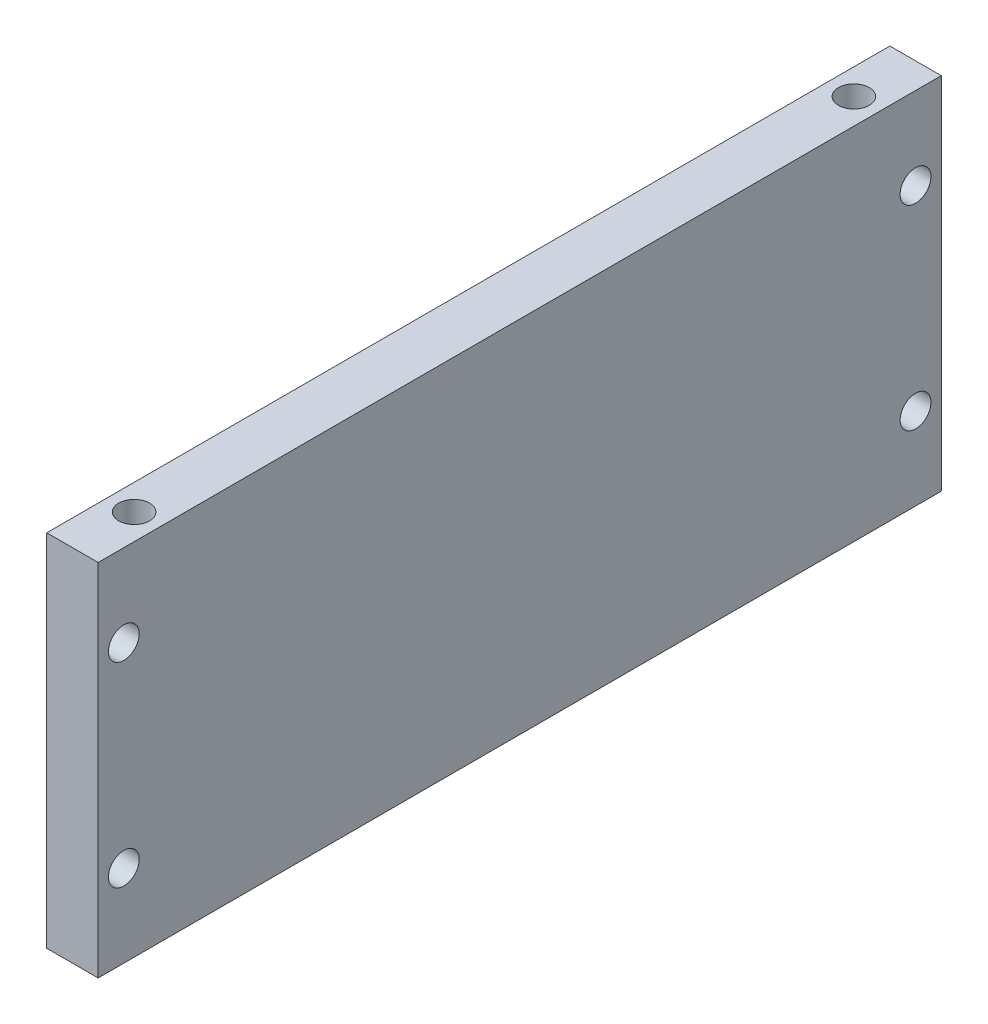
SolidWorks part; units mm, degrees
ref_plane "Front Plane" through (0, 0, 0) normal (0, 0, 1) x (1, 0, 0)
ref_plane "Top Plane" through (0, 0, 0) normal (0, 1, 0) x (1, 0, 0)
ref_plane "Right Plane" through (0, 0, 0) normal (1, 0, 0) x (0, 0, -1)
sketch "Sketch1" plane through (0, 0, 0) normal (1, 0, 0) x (0, 0, -1)
  line L0 (-41, 17.5) -> (41, 17.5)
  line L1 (-41, -17.5) -> (41, -17.5)
  line L2 (-41, -17.5) -> (-41, 17.5)
  line L4 (41, -17.5) -> (41, 17.5)
  line L5 (-41, -17.5) -> (41, 17.5) construction
  line L6 (-41, 17.5) -> (41, -17.5) construction
  point P0 (0, 0)
  dimension "D1" = 35
  dimension "D2" = 82
extrude "Boss-Extrude1" add sketch "Sketch1" along normal blind 5
sketch "Sketch2" plane through (5, 0, 0) normal (1, 0, 0) x (0, 0, -1)
  line L0 (-41, 17.5) -> (-38.5, 17.5) construction
  line L1 (41, 17.5) -> (-41, 17.5) construction
  line L2 (-38.5, 17.5) -> (-38.5, 9.5) construction
  line L3 (2.75, 0) -> (-2.75, 0) construction
  line L4 (0, 2.75) -> (0, -2.75) construction
  circle A0 centre (-38.5, 9.5) radius 1.5
  circle A1 centre (-38.5, -9.5) radius 1.5
  circle A2 centre (38.5, -9.5) radius 1.5
  circle A3 centre (38.5, 9.5) radius 1.5
  dimension "D3" = 3
  dimension "D1" = 2.5
  dimension "D2" = 8
extrude "Cut-Extrude1" cut sketch "Sketch2" against normal blind 4
sketch "Sketch3" plane through (0, -17.5, 0) normal (0, -1, 0) x (1, 0, 0)
  line L0 (2.5, 41) -> (2.5, 35) construction
  line L1 (5, 41) -> (0, 41) construction
  line L2 (2.75, 0) -> (-2.75, 0) construction
  circle A0 centre (2.5, 35) radius 1.5
  circle A1 centre (2.5, -35) radius 1.5
  dimension "D2" = 3
  dimension "D1" = 6
extrude "Cut-Extrude2" cut sketch "Sketch3" against normal blind 4
sketch "Sketch4" plane through (0, 17.5, 0) normal (0, 1, 0) x (1, 0, 0)
  line L0 (2.5, -41) -> (2.5, -35) construction
  line L1 (5, -41) -> (0, -41) construction
  line L2 (-2.75, 0) -> (2.75, 0) construction
  circle A0 centre (2.5, -35) radius 1.5
  circle A1 centre (2.5, 35) radius 1.5
  dimension "D2" = 3
  dimension "D1" = 6
extrude "Cut-Extrude3" cut sketch "Sketch4" against normal blind 4
